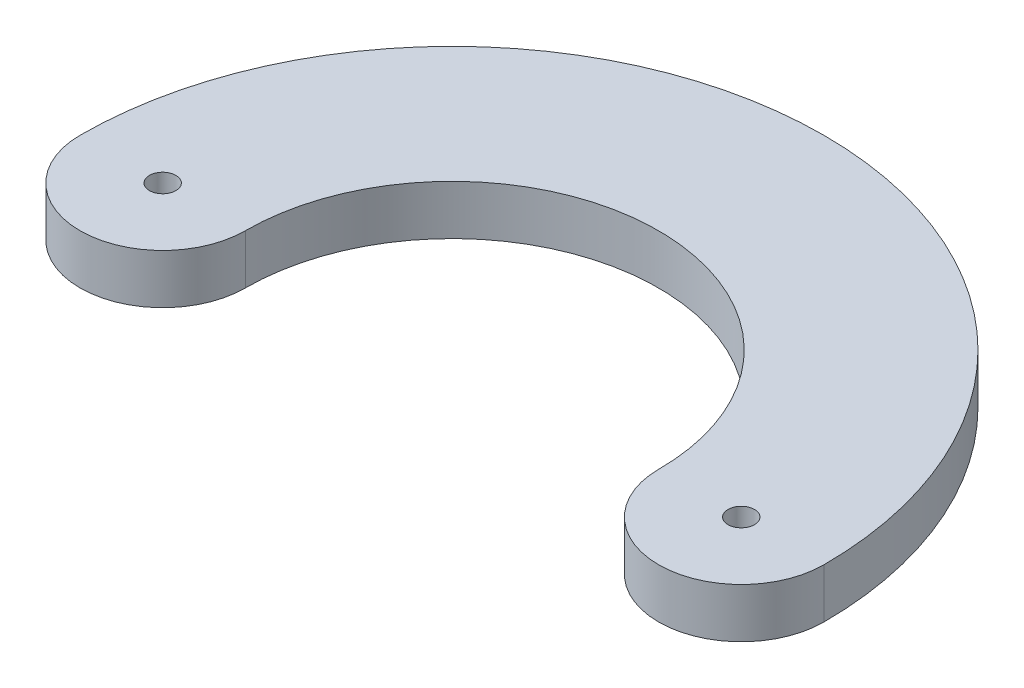
SolidWorks part; units mm, degrees
ref_plane "Front Plane" through (0, 0, 0) normal (0, 0, 1) x (1, 0, 0)
ref_plane "Top Plane" through (0, 0, 0) normal (0, 1, 0) x (1, 0, 0)
ref_plane "Right Plane" through (0, 0, 0) normal (1, 0, 0) x (0, 0, -1)
sketch "Sketch1" plane through (0, 0, 0) normal (0, 1, 0) x (1, 0, 0)
  line L0 (0, 0) -> (-25, 0) construction
  line L1 (-25, 0) -> (-45, 0) construction
  arc A0 (25, 0) -> (-25, 0) centre (0, 0) ccw
  arc A1 (45, 0) -> (-45, 0) centre (0, 0) ccw
  arc A2 (-45, 0) -> (-25, 0) centre (-35, 0) ccw
  arc A3 (25, 0) -> (45, 0) centre (35, 0) ccw
  circle A4 centre (-35, 0) radius 1.6
  circle A5 centre (35, 0) radius 1.6
extrude "Boss-Extrude1" add sketch "Sketch1" along normal blind 6
